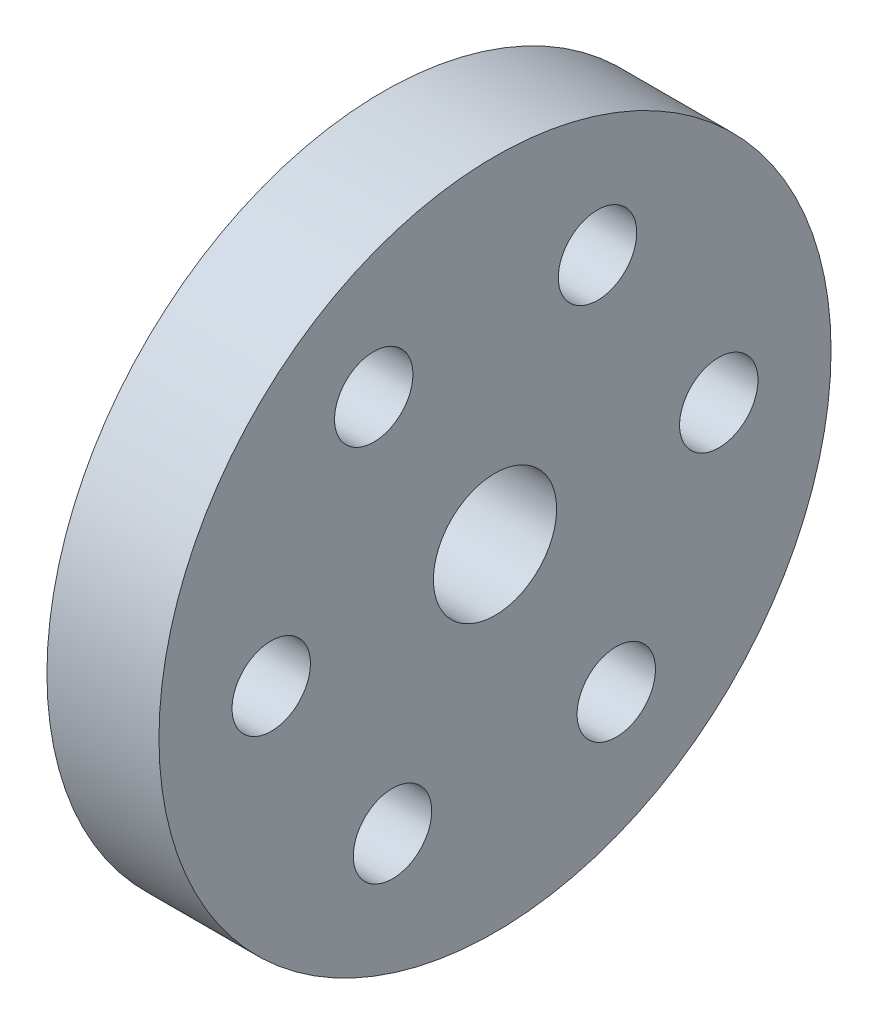
SolidWorks part; units mm, degrees
ref_plane "Front Plane" through (0, 0, 0) normal (0, 0, 1) x (1, 0, 0)
ref_plane "Top Plane" through (0, 0, 0) normal (0, 1, 0) x (1, 0, 0)
ref_plane "Right Plane" through (0, 0, 0) normal (1, 0, 0) x (0, 0, -1)
sketch "Sketch1" plane through (0, 0, 0) normal (1, 0, 0) x (0, 0, -1)
  circle A0 centre (0, 0) radius 15
  circle A1 centre (0, 0) radius 2.75
  dimension "D1" = 30
  dimension "D2" = 5.5
extrude "Boss-Extrude1" add sketch "Sketch1" along normal blind 5
sketch "Sketch3" plane through (5, 0, 0) normal (1, 0, 0) x (0, 0, -1)
  circle A12 centre (9.9883, 0.4834) radius 1.75 construction
  circle A13 centre (5.4128, -8.4084) radius 1.75 construction
  circle A14 centre (-4.5755, -8.8918) radius 1.75 construction
  circle A15 centre (-9.9883, -0.4834) radius 1.75 construction
  circle A16 centre (-5.4128, 8.4084) radius 1.75 construction
  circle A17 centre (4.5755, 8.8918) radius 1.75 construction
  circle A18 centre (9.9883, 0.4834) radius 1.75
  circle A19 centre (5.4128, -8.4084) radius 1.75
  circle A20 centre (-4.5755, -8.8918) radius 1.75
  circle A21 centre (-9.9883, -0.4834) radius 1.75
  circle A22 centre (-5.4128, 8.4084) radius 1.75
  circle A23 centre (4.5755, 8.8918) radius 1.75
extrude "Cut-Extrude1" cut sketch "Sketch3" against normal through all
